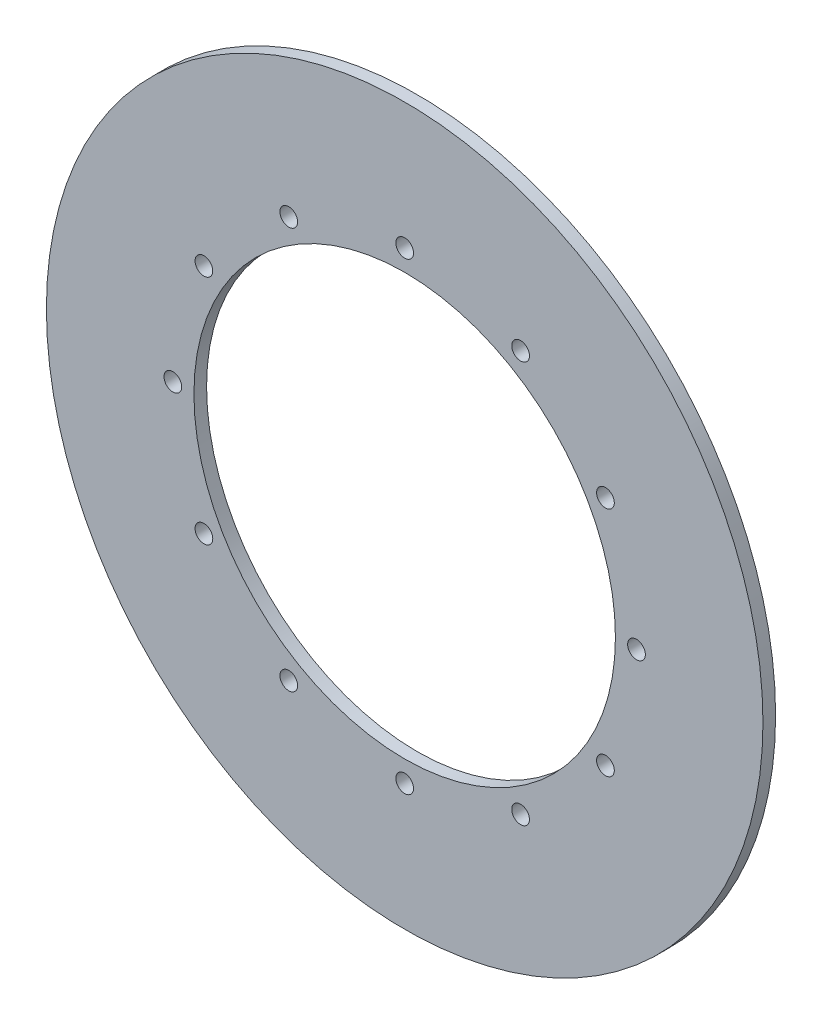
SolidWorks part; units mm, degrees
material "Thornel Mat VMA"
ref_plane "前视基准面" through (0, 0, 0) normal (0, 0, 1) x (1, 0, 0)
ref_plane "上视基准面" through (0, 0, 0) normal (0, 1, 0) x (1, 0, 0)
ref_plane "右视基准面" through (0, 0, 0) normal (1, 0, 0) x (0, 0, -1)
other "Configuration Table"
sketch "草图1" plane through (0, 0, 0) normal (0, 0, 1) x (1, 0, 0)
  circle A0 centre (0, 0) radius 85
  circle A1 centre (0, 0) radius 50
  circle A2 centre (0, 0) radius 55 construction
  circle A3 centre (0, 55) radius 2.1
  circle A4 centre (27.5, 47.6314) radius 2.1
  circle A5 centre (47.6314, 27.5) radius 2.1
  circle A6 centre (55, 0) radius 2.1
  circle A7 centre (47.6314, -27.5) radius 2.1
  circle A8 centre (27.5, -47.6314) radius 2.1
  circle A9 centre (0, -55) radius 2.1
  circle A10 centre (-27.5, -47.6314) radius 2.1
  circle A11 centre (-47.6314, -27.5) radius 2.1
  circle A12 centre (-55, 0) radius 2.1
  circle A13 centre (-47.6314, 27.5) radius 2.1
  circle A14 centre (-27.5, 47.6314) radius 2.1
  point P31 (0, 0)
  dimension "D1" = 100
  dimension "D2" = 170
  dimension "D3" = 110
  dimension "D4" = 4.2
  dimension "D5" = 12
extrude "凸台-拉伸1" add sketch "草图1" along normal blind 3
